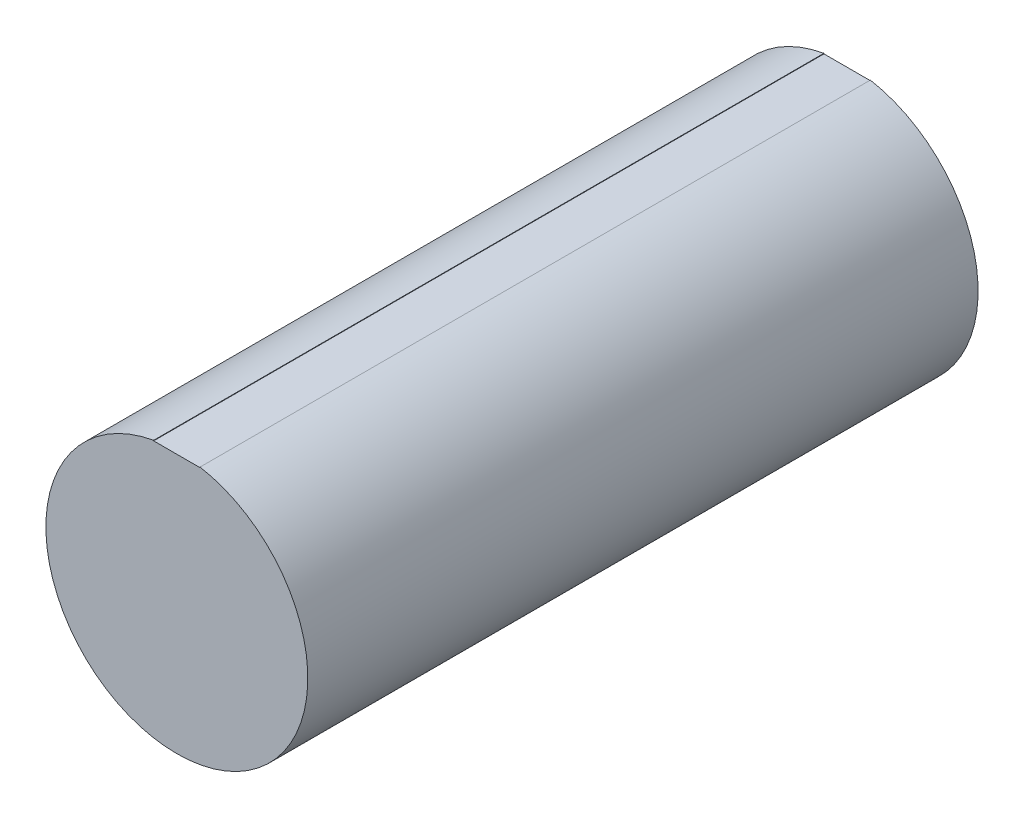
SolidWorks part; units mm, degrees
ref_plane "Alzado" through (0, 0, 0) normal (0, 0, 1) x (1, 0, 0)
ref_plane "Planta" through (0, 0, 0) normal (0, 1, 0) x (1, 0, 0)
ref_plane "Vista lateral" through (0, 0, 0) normal (1, 0, 0) x (0, 0, -1)
sketch "Croquis1" plane through (0, 0, 0) normal (0, 0, 1) x (1, 0, 0)
  circle A0 centre (0, 0) radius 25.4
  dimension "D1" = 50.8
extrude "Saliente-Extruir1" add sketch "Croquis1" along normal blind 130
sketch "Croquis2" plane through (0, 0, 130) normal (0, 0, 1) x (1, 0, 0)
  line L1 (-4.5, 24.9) -> (4.5, 24.9)
  line L2 (-4.5, 24.9) -> (-4.5, 25.9)
  line L3 (-4.5, 25.9) -> (4.5, 25.9)
  line L4 (4.5, 24.9) -> (4.5, 25.9)
  line L5 (-4.5, 24.9) -> (4.5, 25.9) construction
  line L6 (-4.5, 25.9) -> (4.5, 24.9) construction
  circle A0 centre (0, 0) radius 25.4 construction
  point P0 (0, 25.4)
  dimension "D1" = 9
  dimension "D2" = 1
extrude "Cortar-Extruir1" cut sketch "Croquis2" against normal up to surface (130 mm away) up to face at (25.4, 0, 0)
